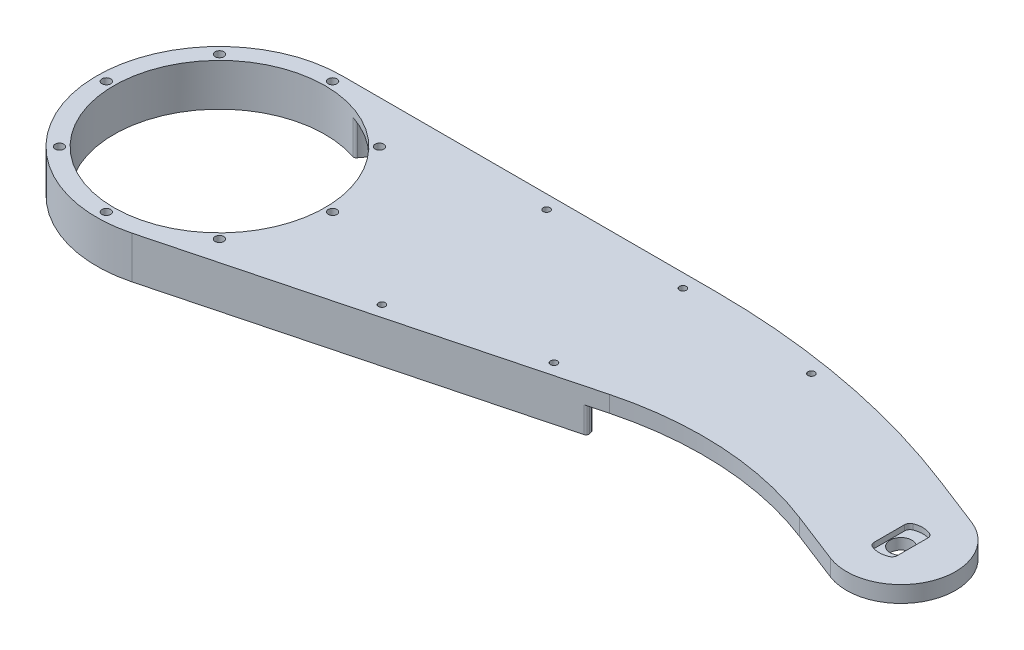
SolidWorks part; units mm, degrees
ref_plane "Спереди" through (0, 0, 0) normal (0, 0, 1) x (1, 0, 0)
ref_plane "Сверху" through (0, 0, 0) normal (0, 1, 0) x (1, 0, 0)
ref_plane "Справа" through (0, 0, 0) normal (1, 0, 0) x (0, 0, -1)
ref_plane "Плоскость4" through (0, 0, 0) normal (0, -1, 0) x (1, 0, 0)
sketch "Эскиз1" plane through (0, 0, 0) normal (0, -1, 0) x (1, 0, 0)
  line L0 (31.7794, 35.0947) -> (32.5393, 37.9968)
  line L1 (32.5393, 37.9968) -> (11.3988, 43.5324)
  line L2 (0, -45) -> (136.6047, -45)
  line L3 (211.069, -33.2121) -> (207.1483, -30.9537)
  line L4 (118.5109, -42) -> (21.8532, -42)
  arc A0 (11.3988, 43.5324) -> (0, -45) centre (0, 0) ccw
  arc A1 (136.6047, -45) -> (210.8334, -35.0433) centre (136.6047, 236.6697) ccw
  arc A2 (210.8334, -35.0433) -> (211.069, -33.2121) centre (210.5698, -34.0786) ccw
  arc A3 (207.1483, -30.9537) -> (200.8795, -34.4863) centre (197.8811, -21.8368) cw
  arc A4 (200.8795, -34.4863) -> (141.6391, -41.9545) centre (136.6047, 236.6697) cw
  arc A5 (141.6391, -41.9545) -> (133.2738, -37.7018) centre (141.4585, -31.9562) cw
  arc A6 (133.2738, -37.7018) -> (126.7174, -37.7143) centre (130, -40) ccw
  arc A7 (126.7174, -37.7143) -> (118.5109, -42) centre (118.5109, -32) cw
  arc A8 (21.8532, -42) -> (12.9365, -36.5268) centre (21.8532, -32) cw
  arc A9 (12.9365, -36.5268) -> (21.7671, 32.0587) centre (0, 0) ccw
  arc A10 (21.7671, 32.0587) -> (31.7794, 35.0947) centre (29.2463, 25.4208) cw
extrude "Бобышка-Вытянуть1" add sketch "Эскиз1" against normal blind 9.5
sketch "Эскиз2" plane through (21.1405, 0, -5.5356) normal (0.9674, 0, -0.2533) x (-0.2533, 0, -0.9674)
  line L0 (-42, 0) -> (-45, 0)
  line L1 (-45, 0) -> (-45, 9.5)
  line L2 (-45, 9.5) -> (-42, 9.5)
  line L3 (-42, 9.5) -> (-42, 0)
extrude "Бобышка-Вытянуть2" add sketch "Эскиз2" along normal blind 115.0557
sketch "Эскиз3" plane through (0, 9.5, 0) normal (0, 1, 0) x (-1, 0, 0)
  line L0 (0, -45) -> (-136.6047, -45)
  line L1 (-238.5994, -25.8849) -> (-257.2421, -18.6427)
  line L2 (-242.7579, 18.6427) -> (-187.8755, -2.6774)
  line L3 (-187.8755, -2.6774) -> (-11.3988, 43.5324)
  arc A0 (-11.3988, 43.5324) -> (0, -45) centre (0, 0) cw
  arc A1 (-136.6047, -45) -> (-238.5994, -25.8849) centre (-136.6047, 236.6697) cw
  arc A2 (-257.2421, -18.6427) -> (-242.7579, 18.6427) centre (-250, 0) cw
extrude "Бобышка-Вытянуть3" add sketch "Эскиз3" along normal blind 6
sketch "Эскиз4" plane through (0, 9.5, 0) normal (0, -1, 0) x (1, 0, 0)
  line L0 (201.1741, -9.2608) -> (31.7794, 35.0947)
  line L1 (21.8532, -42) -> (118.5109, -42)
  arc A0 (31.7794, 35.0947) -> (21.7671, 32.0587) centre (29.2463, 25.4208) ccw
  arc A1 (21.7671, 32.0587) -> (12.9365, -36.5268) centre (0, 0) cw
  arc A2 (12.9365, -36.5268) -> (21.8532, -42) centre (21.8532, -32) ccw
  arc A3 (118.5109, -42) -> (126.7174, -37.7143) centre (118.5109, -32) ccw
  arc A4 (126.7174, -37.7143) -> (133.2738, -37.7018) centre (130, -40) cw
  arc A5 (133.2738, -37.7018) -> (141.6391, -41.9545) centre (141.4585, -31.9562) ccw
  arc A6 (141.6391, -41.9545) -> (200.8795, -34.4863) centre (136.6047, 236.6697) ccw
  arc A7 (200.8795, -34.4863) -> (201.1741, -9.2608) centre (197.8811, -21.8368) ccw
extrude "Вырез-Вытянуть1" cut sketch "Эскиз4" against normal blind 3
sketch "Эскиз5" plane through (0, 12.5, 0) normal (0, -1, 0) x (1, 0, 0)
  line L0 (69.3922, 25.2459) -> (91.621, 19.4253)
  arc A0 (76.2455, 19.0212) -> (69.3922, 25.2459) centre (66.8591, 15.572) ccw
  arc A1 (91.621, 19.4253) -> (82.5966, 17.3581) centre (89.088, 9.7515) ccw
  arc A2 (82.5966, 17.3581) -> (76.2455, 19.0212) centre (80, 20.4008) cw
extrude "Бобышка-Вытянуть4" add sketch "Эскиз5" along normal blind 12.5
sketch "Эскиз6" plane through (0, 12.5, 0) normal (0, -1, 0) x (1, 0, 0)
  line L0 (119.3922, 12.1535) -> (141.621, 6.333)
  arc A0 (126.2455, 5.9288) -> (119.3922, 12.1535) centre (116.8591, 2.4797) ccw
  arc A1 (141.621, 6.333) -> (132.5966, 4.2658) centre (139.088, -3.3409) ccw
  arc A2 (132.5966, 4.2658) -> (126.2455, 5.9288) centre (130, 7.3085) cw
extrude "Бобышка-Вытянуть5" add sketch "Эскиз6" along normal blind 12.5
sketch "Эскиз7" plane through (0, 12.5, 0) normal (0, -1, 0) x (1, 0, 0)
  arc A0 (169.3505, -40.0694) -> (177.0946, -34.6607) centre (168.1755, -30.1387) ccw
  arc A1 (177.0946, -34.6607) -> (183.4802, -33.6307) centre (180.6622, -36.4696) cw
  arc A2 (183.4802, -33.6307) -> (192.5321, -36.3302) centre (190.5252, -26.5336) ccw
  arc A3 (192.5321, -36.3302) -> (169.3505, -40.0694) centre (136.6047, 236.6697) cw
extrude "Бобышка-Вытянуть6" add sketch "Эскиз7" along normal blind 12.5
sketch "Эскиз8" plane through (0, 12.5, 0) normal (0, -1, 0) x (1, 0, 0)
  line L0 (91.4891, -42) -> (68.5109, -42)
  arc A0 (83.2826, -37.7143) -> (91.4891, -42) centre (91.4891, -32) ccw
  arc A1 (68.5109, -42) -> (76.7174, -37.7143) centre (68.5109, -32) ccw
  arc A2 (76.7174, -37.7143) -> (83.2826, -37.7143) centre (80, -40) cw
extrude "Бобышка-Вытянуть7" add sketch "Эскиз8" along normal blind 12.5
sketch "Эскиз9" plane through (0, 15.5, 0) normal (0, 1, 0) x (-1, 0, 0)
  line L0 (-245.75, -6.7777) -> (-245.75, 6.7777)
  line L1 (-254.25, 6.7777) -> (-254.25, -6.7777)
  arc A0 (-254.25, -6.7777) -> (-245.75, -6.7777) centre (-250, 0) ccw
  arc A1 (-245.75, 6.7777) -> (-254.25, 6.7777) centre (-250, 0) ccw
extrude "Вырез-Вытянуть2" cut sketch "Эскиз9" against normal blind 2
ref_plane "Плоскость5" through (0, 0, 0) normal (0, 0, -1) x (-1, 0, 0)
sketch "Эскиз10" plane through (0, 0, 0) normal (0, 0, -1) x (-1, 0, 0)
  line L0 (-38.75, 0) -> (0, 0)
  line L1 (0, 0) -> (0, 15.5)
  line L2 (0, 15.5) -> (-38.75, 15.5)
  line L3 (-38.75, 15.5) -> (-38.75, 0)
  line L4 (0, 0) -> (0, 15.5) construction
revolve "Вырез-Повернуть1" cut sketch "Эскиз10" angle 360 about L4
hole_wizard "Диаметр отверстия Ø8.0 (8)1" positions "Эскиз12" profile "Эскиз11" hole size "Ø8.0" standard "Ansi Metric"
sketch "Эскиз12" plane through (0, 9.5, 0) normal (0, -1, 0) x (-1, 0, 0)
  point P0 (-250, 0)
sketch "Эскиз11" plane through (250, 9.5, 0) normal (1, 0, 0) x (0, 0, -1)
  line L0 (0, 0) -> (0, 6)
  line L1 (0, 6) -> (4, 6)
  line L2 (4, 6) -> (4, 0)
  line L5 (4, 0) -> (0, 0)
  line L11 (0, -6.35) -> (0, 107.95) construction
  dimension "Диаметр сквозного отверстия" = 8
  dimension "Глубина сквозного отверстия" = 6
hole_wizard "Диаметр отверстия Ø2.5 (2.5)1" positions "Эскиз14" profile "Эскиз13" hole size "Ø2.5" standard "Ansi Metric"
sketch "Эскиз14" plane through (0, 15.5, 0) normal (0, 1, 0) x (1, 0, 0)
  point P0 (130, -7.3085)
  point P1 (130, 40)
  point P2 (80, -20.4008)
  point P3 (180.6622, 36.4696)
  point P4 (80, 40)
sketch "Эскиз13" plane through (130, 15.5, 7.3085) normal (1, 0, 0) x (0, 0, 1)
  line L0 (0, 0) -> (0, 15.5)
  line L1 (0, 15.5) -> (1.25, 15.5)
  line L2 (1.25, 15.5) -> (1.25, 0)
  line L5 (1.25, 0) -> (0, 0)
  line L11 (0, -6.35) -> (0, 107.95) construction
  dimension "Диаметр сквозного отверстия" = 2.5
  dimension "Глубина сквозного отверстия" = 15.5
hole_wizard "Диаметр отверстия Ø3.2 (3.2)1" positions "Эскиз16" profile "Эскиз15" hole size "Ø3.2" standard "Ansi Metric"
sketch "Эскиз16" plane through (0, 15.5, 0) normal (0, 1, 0) x (1, 0, 0)
  point P0 (29.3449, 29.3449)
  point P1 (41.5, 0)
  point P2 (29.3449, -29.3449)
sketch "Эскиз15" plane through (29.3449, 15.5, -29.3449) normal (1, 0, 0) x (0, 0, 1)
  line L0 (0, 0) -> (0, 15.5)
  line L1 (0, 15.5) -> (1.6, 15.5)
  line L2 (1.6, 15.5) -> (1.6, 0)
  line L5 (1.6, 0) -> (0, 0)
  line L11 (0, -6.35) -> (0, 107.95) construction
  dimension "Диаметр сквозного отверстия" = 3.2
  dimension "Глубина сквозного отверстия" = 15.5
hole_wizard "Диаметр отверстия Ø3.2 (3.2)2" positions "Эскиз18" profile "Эскиз17" hole size "Ø3.2" standard "Ansi Metric"
sketch "Эскиз18" plane through (0, 15.5, 0) normal (0, 1, 0) x (1, 0, 0)
  point P0 (-29.3449, 29.3449)
  point P1 (0, 41.5)
  point P2 (0, -41.5)
  point P3 (-29.3449, -29.3449)
  point P4 (-41.5, 0)
sketch "Эскиз17" plane through (-29.3449, 15.5, -29.3449) normal (1, 0, 0) x (0, 0, 1)
  line L0 (0, 0) -> (0, 15.5)
  line L1 (0, 15.5) -> (1.6, 15.5)
  line L2 (1.6, 15.5) -> (1.6, 0)
  line L5 (1.6, 0) -> (0, 0)
  line L11 (0, -6.35) -> (0, 107.95) construction
  dimension "Диаметр сквозного отверстия" = 3.2
  dimension "Глубина сквозного отверстия" = 15.5
fillet "Скругление1" radius 1 5 edges at (21.7671, 6.25, 32.0587) (12.9365, 6.25, -36.5268) (207.1483, 4.75, -30.9537) (143.0826, 4.75, 5.9503) (143.8426, 4.75, 8.8524)
fillet "Скругление2" radius 2 4 edges at (254.25, 14.5, -6.7777) (254.25, 14.5, 6.7777) (245.75, 14.5, 6.7777) (245.75, 14.5, -6.7777)
fillet "Скругление3" radius 120 1 edges at (187.8755, 12.5, -2.6774)
